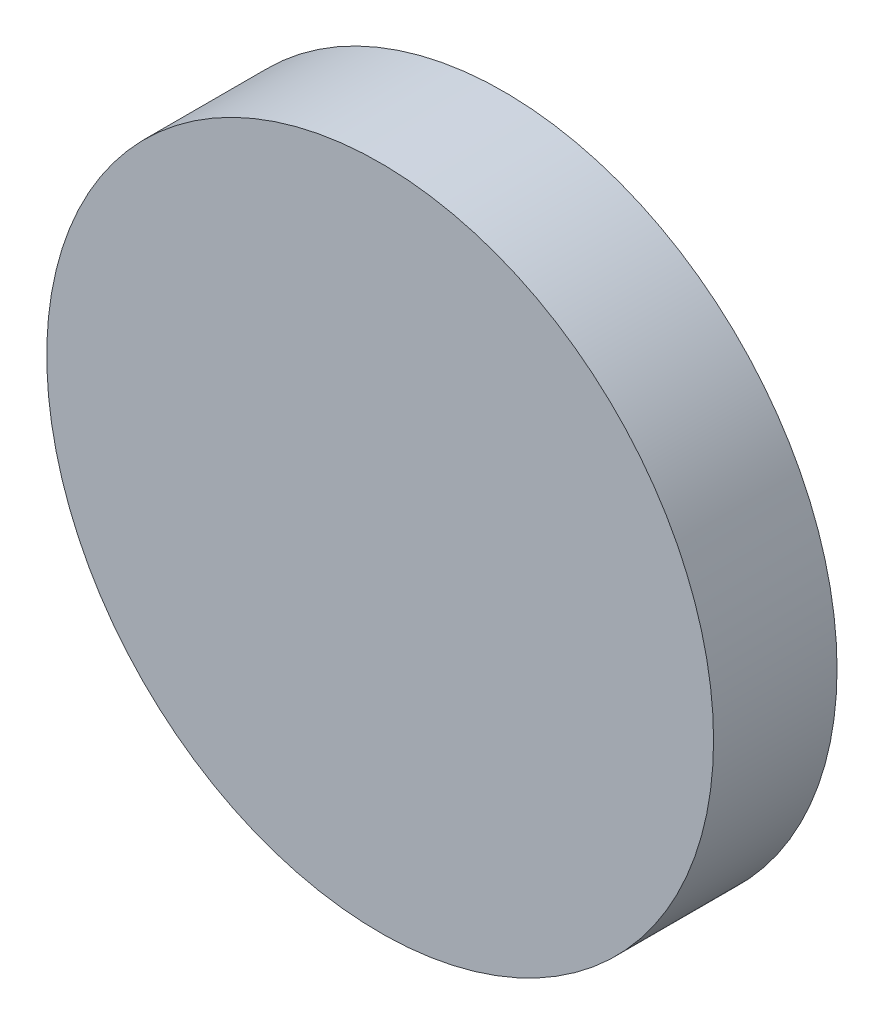
SolidWorks part; units mm, degrees
ref_plane "Front Plane" through (0, 0, 0) normal (0, 0, 1) x (1, 0, 0)
ref_plane "Top Plane" through (0, 0, 0) normal (0, 1, 0) x (1, 0, 0)
ref_plane "Right Plane" through (0, 0, 0) normal (1, 0, 0) x (0, 0, -1)
sketch "Sketch1" plane through (0, 0, 0) normal (0, 0, 1) x (1, 0, 0)
  circle A0 centre (0, 0) radius 27
  dimension "D1" = 54
extrude "Boss-Extrude1" add sketch "Sketch1" along normal mid plane 10
sketch "Sketch2" plane through (0, 0, -5) normal (0, 0, -1) x (-1, 0, 0)
  circle A0 centre (0, 0) radius 10
  dimension "D1" = 20
extrude "Boss-Extrude2" add sketch "Sketch2" along normal blind 2.5
sketch "Sketch3" plane through (0, 0, -7.5) normal (0, 0, -1) x (-1, 0, 0)
  line L0 (0, 2.7) -> (0, -2.7) construction
  line L1 (-1.9534, -1.9) -> (1.9534, -1.9)
  line L2 (-1.9534, 1.9) -> (1.9534, 1.9)
  arc A0 (-1.9534, 1.9) -> (-1.9534, -1.9) centre (0, 0) ccw
  arc A1 (1.9534, -1.9) -> (1.9534, 1.9) centre (0, 0) ccw
  dimension "D1" = 5.45
  dimension "D2" = 1.9
  dimension "D3" = 1.9
extrude "Cut-Extrude1" cut sketch "Sketch3" against normal blind 9
